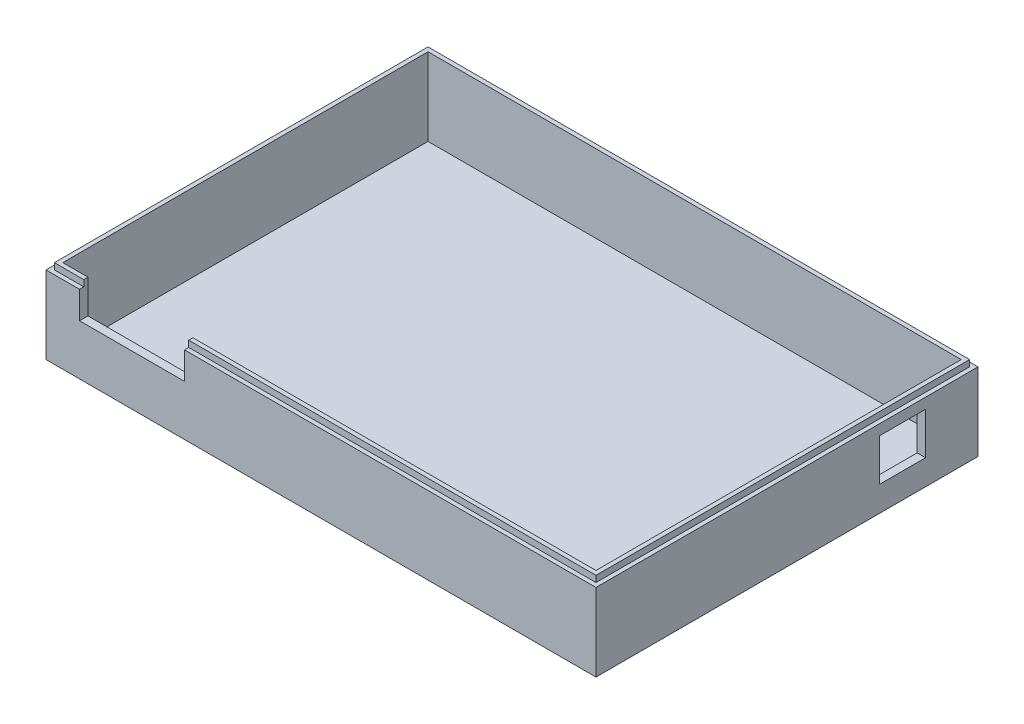
SolidWorks part; units mm, degrees
ref_plane "Front Plane" through (0, 0, 0) normal (0, 0, 1) x (1, 0, 0)
ref_plane "Top Plane" through (0, 0, 0) normal (0, 1, 0) x (1, 0, 0)
ref_plane "Right Plane" through (0, 0, 0) normal (1, 0, 0) x (0, 0, -1)
sketch "Sketch1" plane through (0, 0, 0) normal (0, 1, 0) x (1, 0, 0)
  line L1 (-63.5, -43.5) -> (63.5, -43.5)
  line L2 (-63.5, -43.5) -> (-63.5, 43.5)
  line L3 (-63.5, 43.5) -> (63.5, 43.5)
  line L4 (63.5, -43.5) -> (63.5, 43.5)
  line L5 (-63.5, -43.5) -> (63.5, 43.5) construction
  line L6 (-63.5, 43.5) -> (63.5, -43.5) construction
  point P0 (0, 0)
  dimension "D1" = 127
  dimension "D2" = 87
extrude "Boss-Extrude1" add sketch "Sketch1" along normal blind 1.5
sketch "Sketch3" plane through (0, 0, 0) normal (0, 1, 0) x (1, 0, 0)
  line L8 (-65.5, 45.5) -> (-65.5, -45.5)
  line L9 (-65.5, -45.5) -> (65.5, -45.5)
  line L10 (65.5, -45.5) -> (65.5, 45.5)
  line L11 (65.5, 45.5) -> (-65.5, 45.5)
  line L12 (-65.5, 45.5) -> (-65.5, -45.5)
  line L13 (-65.5, -45.5) -> (65.5, -45.5)
  line L14 (65.5, -45.5) -> (65.5, 45.5)
  line L15 (65.5, 45.5) -> (-65.5, 45.5)
  line L20 (-63.5, -43.5) -> (63.5, -43.5)
  line L21 (63.5, -43.5) -> (63.5, 43.5)
  line L22 (63.5, 43.5) -> (-63.5, 43.5)
  line L23 (-63.5, 43.5) -> (-63.5, -43.5)
  line L24 (-63.5, -43.5) -> (63.5, -43.5)
  line L25 (63.5, -43.5) -> (63.5, 43.5)
  line L26 (63.5, 43.5) -> (-63.5, 43.5)
  line L27 (-63.5, 43.5) -> (-63.5, -43.5)
  dimension "D1" = 2
  dimension "D2" = 0
extrude "Boss-Extrude2" add sketch "Sketch3" along normal blind 20
sketch "Sketch4" plane through (0, 0, 45.5) normal (0, 0, 1) x (1, 0, 0)
  line L0 (-65.5, 0) -> (65.5, 0) construction
  line L1 (-57.5, 22) -> (-32.5, 22)
  line L2 (-57.5, 22) -> (-57.5, 12)
  line L3 (-57.5, 12) -> (-32.5, 12)
  line L4 (-32.5, 22) -> (-32.5, 12)
  line L5 (-57.5, 22) -> (-32.5, 12) construction
  line L6 (-57.5, 12) -> (-32.5, 22) construction
  line L7 (-65.5, 20) -> (-65.5, 0) construction
  point P0 (-45, 17)
  dimension "D1" = 12
  dimension "D2" = 25
  dimension "D3" = 8
  dimension "D4" = 10
extrude "Cut-Extrude1" cut sketch "Sketch4" against normal up to next
sketch "Sketch5" plane through (65.5, 0, 0) normal (1, 0, 0) x (0, 0, -1)
  line L0 (45.5, 20) -> (45.5, 0) construction
  line L1 (22, 6) -> (33, 6)
  line L2 (22, 6) -> (22, 16)
  line L3 (22, 16) -> (33, 16)
  line L4 (33, 6) -> (33, 16)
  line L5 (22, 6) -> (33, 16) construction
  line L6 (22, 16) -> (33, 6) construction
  line L7 (-45.5, 0) -> (45.5, 0) construction
  point P0 (27.5, 11)
  dimension "D1" = 12.5
  dimension "D2" = 6
  dimension "D3" = 11
  dimension "D4" = 10
extrude "Cut-Extrude2" cut sketch "Sketch5" against normal up to next
sketch "Sketch6" plane through (0, 20, 0) normal (0, 1, 0) x (1, 0, 0)
  line L12 (-57.5, -44.5) -> (-64.5, -44.5)
  line L13 (-64.5, -44.5) -> (-64.5, 44.5)
  line L14 (-64.5, 44.5) -> (64.5, 44.5)
  line L15 (64.5, 44.5) -> (64.5, -44.5)
  line L16 (64.5, -44.5) -> (-32.5, -44.5)
  line L24 (-57.5, -45.5) -> (-57.5, -43.5)
  line L25 (-57.5, -43.5) -> (-63.5, -43.5)
  line L26 (-63.5, -43.5) -> (-63.5, 43.5)
  line L27 (-63.5, 43.5) -> (63.5, 43.5)
  line L28 (63.5, 43.5) -> (63.5, -43.5)
  line L29 (63.5, -43.5) -> (-32.5, -43.5)
  line L30 (-32.5, -43.5) -> (-32.5, -45.5)
  line L31 (-32.5, -45.5) -> (65.5, -45.5)
  line L32 (65.5, -45.5) -> (65.5, 45.5)
  line L33 (65.5, 45.5) -> (-65.5, 45.5)
  line L34 (-65.5, 45.5) -> (-65.5, -45.5)
  line L35 (-65.5, -45.5) -> (-57.5, -45.5)
  line L36 (-57.5, -45.5) -> (-57.5, -44.5)
  line L42 (-32.5, -44.5) -> (-32.5, -45.5)
  line L43 (-32.5, -45.5) -> (65.5, -45.5)
  line L44 (65.5, -45.5) -> (65.5, 45.5)
  line L45 (65.5, 45.5) -> (-65.5, 45.5)
  line L46 (-65.5, 45.5) -> (-65.5, -45.5)
  line L47 (-65.5, -45.5) -> (-57.5, -45.5)
  dimension "D1" = 0
extrude "Cut-Extrude3" cut sketch "Sketch6" against normal blind 1.5
